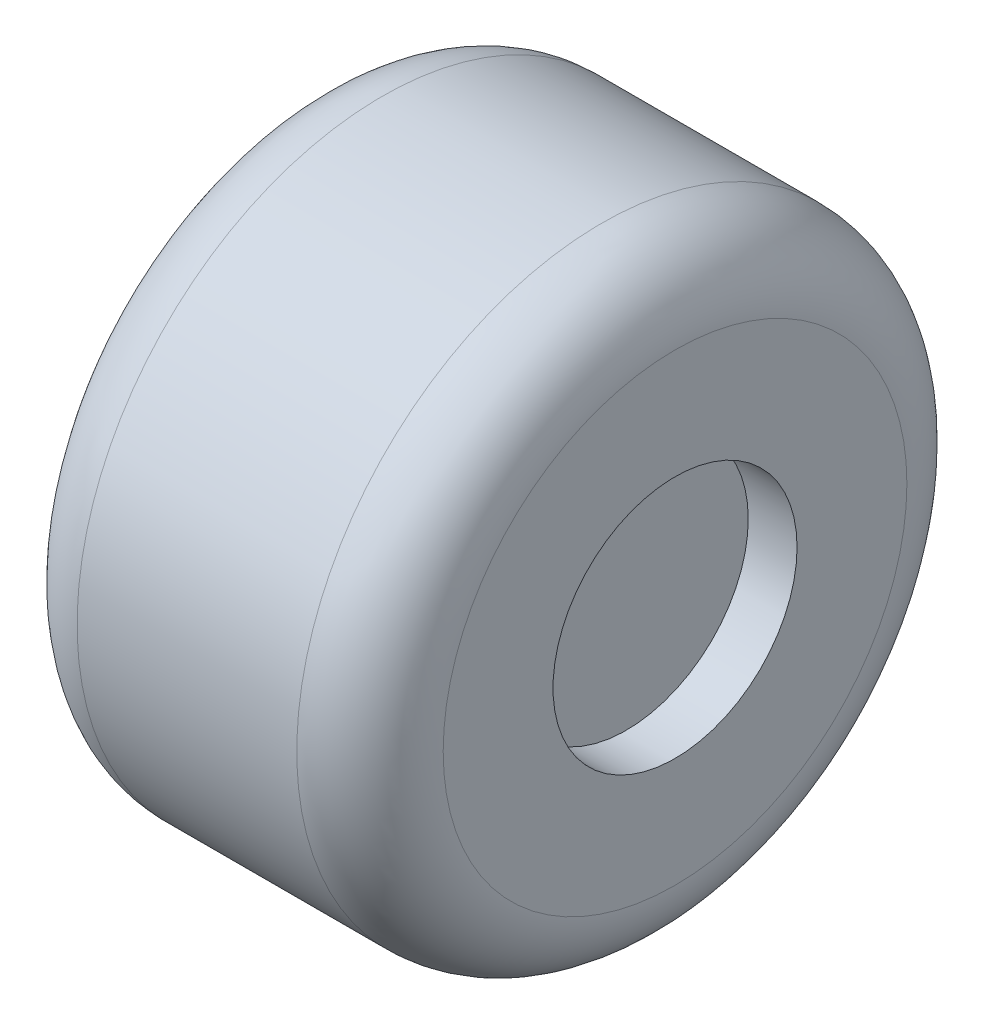
SolidWorks part; units mm, degrees
ref_plane "Front Plane" through (0, 0, 0) normal (0, 0, 1) x (1, 0, 0)
ref_plane "Top Plane" through (0, 0, 0) normal (0, 1, 0) x (1, 0, 0)
ref_plane "Right Plane" through (0, 0, 0) normal (1, 0, 0) x (0, 0, -1)
sketch "Sketch1" plane through (0, 0, 0) normal (1, 0, 0) x (0, 0, -1)
  circle A0 centre (0, 0) radius 125
  dimension "D1" = 250
extrude "Boss-Extrude1" add sketch "Sketch1" along normal mid plane 150
fillet "Fillet1" radius 30 2 edges at (-75, 0, -125) (75, 0, -125)
sketch "Sketch2" plane through (75, 0, 0) normal (1, 0, 0) x (0, 0, -1)
  circle A0 centre (0, 0) radius 50
  dimension "D1" = 100
extrude "Cut-Extrude1" cut sketch "Sketch2" against normal blind 20
sketch "Sketch3" plane through (-75, 0, 0) normal (-1, 0, 0) x (0, 0, 1)
  circle A0 centre (0, 0) radius 30
  dimension "D1" = 60
extrude "Cut-Extrude2" cut sketch "Sketch3" against normal blind 50
